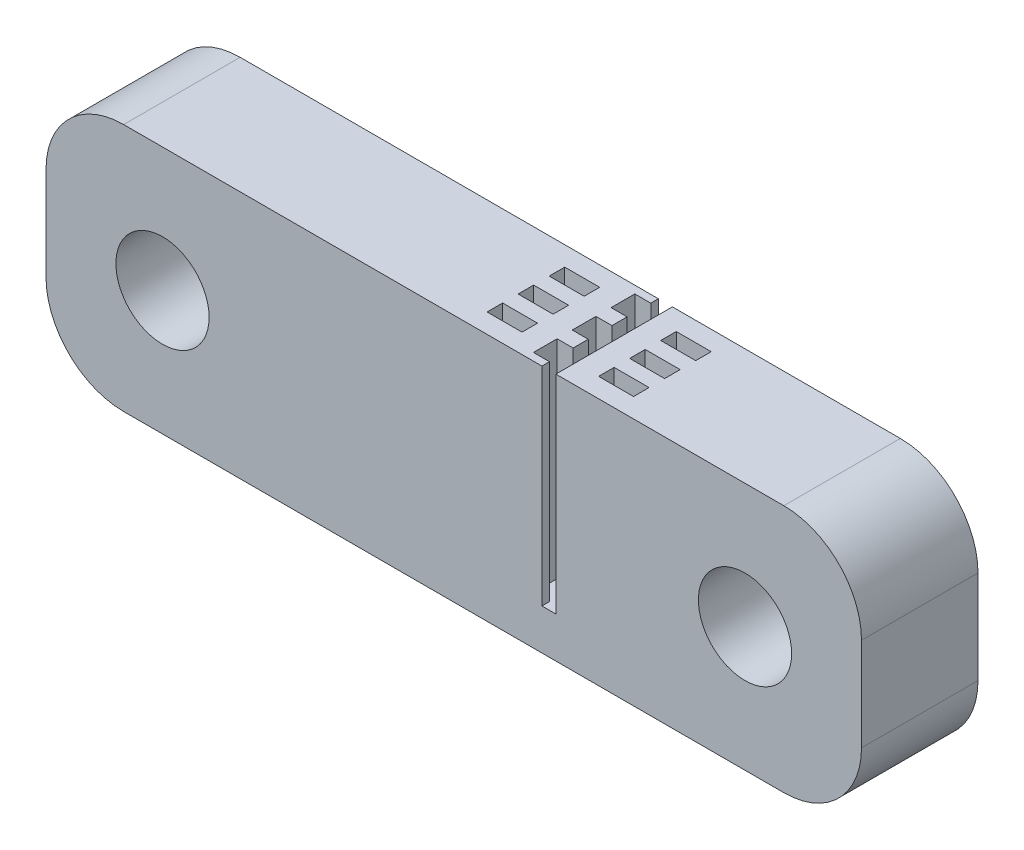
SolidWorks part; units mm, degrees
material "PEI"
ref_plane "前视基准面" through (0, 0, 0) normal (0, 0, 1) x (1, 0, 0)
ref_plane "上视基准面" through (0, 0, 0) normal (0, 1, 0) x (1, 0, 0)
ref_plane "右视基准面" through (0, 0, 0) normal (1, 0, 0) x (0, 0, -1)
sketch "草图1" plane through (0, 0, 0) normal (0, 0, 1) x (1, 0, 0)
  line L1 (-42.5, 16) -> (42.5, 16)
  line L2 (-52.5, 6) -> (-52.5, -6)
  line L3 (-42.5, -16) -> (42.5, -16)
  line L4 (52.5, 6) -> (52.5, -6)
  line L5 (-52.5, 16) -> (52.5, -16) construction
  line L6 (-52.5, -16) -> (52.5, 16) construction
  circle A0 centre (-37.5, 0) radius 6
  circle A1 centre (37.5, 0) radius 6
  arc A2 (-52.5, 6) -> (-42.5, 16) centre (-42.5, 6) cw
  arc A3 (-42.5, -16) -> (-52.5, -6) centre (-42.5, -6) cw
  arc A4 (52.5, 6) -> (42.5, 16) centre (42.5, 6) ccw
  arc A5 (42.5, -16) -> (52.5, -6) centre (42.5, -6) ccw
  point P0 (0, 0)
  dimension "D3" = 12
  dimension "D4" = 12
  dimension "D6" = 0
  dimension "D9" = 10
  dimension "D10" = 10
  dimension "D11" = 10
  dimension "D12" = 10
  dimension "D1" = 105
  dimension "D2" = 32
  dimension "D5" = 0
  dimension "D7" = 37.5
  dimension "D8" = 37.5
extrude "凸台-拉伸1" add sketch "草图1" along normal mid plane 15
sketch "草图2" plane through (0, 16, 0) normal (0, 1, 0) x (1, 0, 0)
  line L0 (42.5, 7.5) -> (-42.5, 7.5) construction
  line L1 (42.5, -7.5) -> (-42.5, -7.5) construction
  line L2 (13.15, 7.5) -> (11.35, 7.5)
  line L3 (13.15, 7.5) -> (13.15, -7.5)
  line L4 (13.15, -7.5) -> (11.35, -7.5)
  line L5 (11.35, 7.5) -> (11.35, 6.52)
  line L7 (11.35, 3.47) -> (11.35, 1.52)
  line L8 (9.29, 6.52) -> (11.35, 6.52)
  line L9 (9.29, 6.52) -> (9.29, 3.47)
  line L10 (9.29, 3.47) -> (11.35, 3.47)
  line L12 (9.29, 1.52) -> (11.35, 1.52)
  line L13 (9.29, 1.52) -> (9.29, -1.53)
  line L14 (9.29, -1.53) -> (11.35, -1.53)
  line L16 (9.29, -3.48) -> (11.35, -3.48)
  line L17 (9.29, -3.48) -> (9.29, -6.53)
  line L18 (9.29, -6.53) -> (11.35, -6.53)
  line L20 (11.35, -1.53) -> (11.35, -3.48)
  line L21 (11.35, -6.53) -> (11.35, -7.5)
  point P17 (10.32, 3.47)
  dimension "D1" = 11.35
  dimension "D2" = 1.8
  dimension "D3" = 0.98
  dimension "D4" = 3.05
  dimension "D5" = 2.06
  dimension "D6" = 1.95
  dimension "D7" = 3.05
  dimension "D8" = 2.06
  dimension "D10" = 3.05
  dimension "D11" = 2.06
  dimension "D12" = 1.95
extrude "切除-拉伸1" cut sketch "草图2" against normal blind 26.75 contours L20 L16 L17 L18 L21 L4 L3 L2 L5 L8 L9 L10 L7 L12 L13 L14
sketch "草图4" plane through (0, 16, 0) normal (0, 1, 0) x (1, 0, 0)
  line L0 (11.35, 7.5) -> (-42.5, 7.5) construction
  line L1 (1.79, 5) -> (6.29, 5)
  line L2 (1.79, 5) -> (1.79, 3)
  line L3 (1.79, 3) -> (6.29, 3)
  line L4 (6.29, 5) -> (6.29, 3)
  line L5 (1.79, 1) -> (6.29, 1)
  line L6 (1.79, 1) -> (1.79, -1)
  line L7 (1.79, -1) -> (6.29, -1)
  line L8 (6.29, 1) -> (6.29, -1)
  line L9 (1.79, -3) -> (6.29, -3)
  line L10 (1.79, -3) -> (1.79, -5)
  line L11 (1.79, -5) -> (6.29, -5)
  line L12 (6.29, -3) -> (6.29, -5)
  line L13 (16.15, 5) -> (20.65, 5)
  line L14 (16.15, 5) -> (16.15, 3)
  line L15 (16.15, 3) -> (20.65, 3)
  line L16 (20.65, 5) -> (20.65, 3)
  line L17 (16.15, 1) -> (20.65, 1)
  line L18 (16.15, 1) -> (16.15, -1)
  line L19 (16.15, -1) -> (20.65, -1)
  line L20 (20.65, 1) -> (20.65, -1)
  line L21 (16.15, -3) -> (20.65, -3)
  line L22 (16.15, -3) -> (16.15, -5)
  line L23 (16.15, -5) -> (20.65, -5)
  line L24 (20.65, -3) -> (20.65, -5)
  line L26 (42.5, 7.5) -> (13.15, 7.5) construction
  line L27 (9.29, 6.52) -> (9.29, 3.47) construction
  line L28 (13.15, 7.5) -> (13.15, -7.5) construction
  dimension "D1" = 2
  dimension "D2" = 2
  dimension "D3" = 2
  dimension "D4" = 4.5
  dimension "D5" = 4.5
  dimension "D6" = 4.5
  dimension "D7" = 4.5
  dimension "D8" = 4.5
  dimension "D9" = 4.5
  dimension "D10" = 2
  dimension "D11" = 2
  dimension "D12" = 2
  dimension "D13" = 2.5
  dimension "D14" = 2
  dimension "D15" = 2
  dimension "D16" = 2.5
  dimension "D17" = 2
  dimension "D18" = 2
  dimension "D19" = 3
  dimension "D20" = 3
extrude "切除-拉伸2" cut sketch "草图4" against normal blind 7
